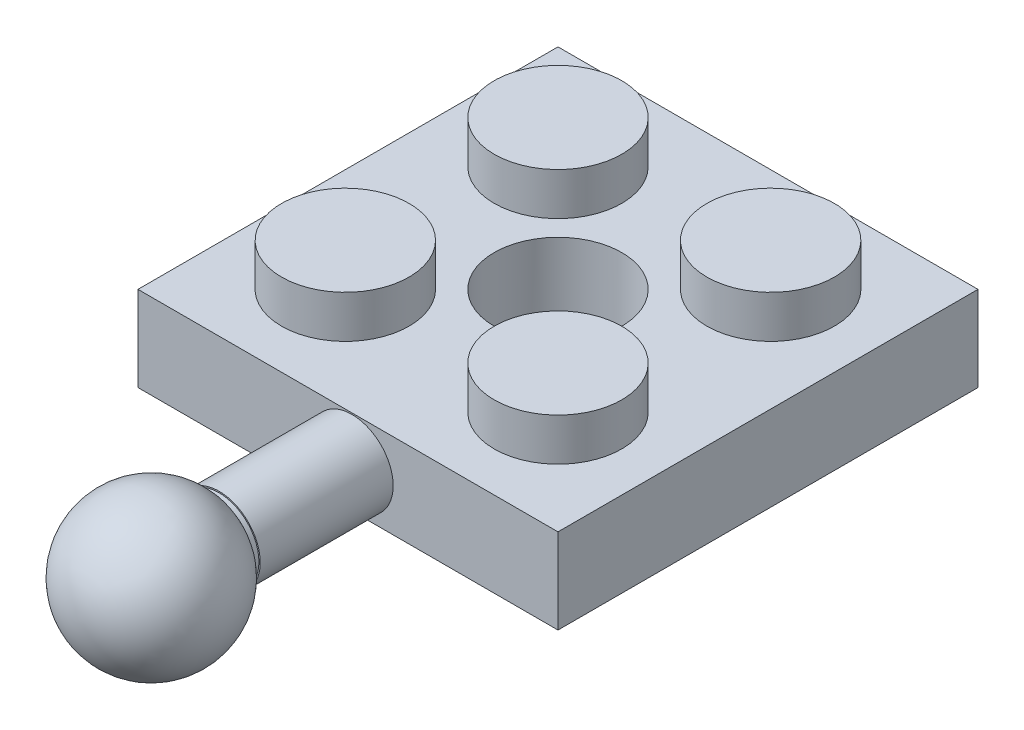
SolidWorks part; units mm, degrees
material "ABS"
ref_plane "Front Plane" through (0, 0, 0) normal (0, 0, 1) x (1, 0, 0)
ref_plane "Top Plane" through (0, 0, 0) normal (0, 1, 0) x (1, 0, 0)
ref_plane "Right Plane" through (0, 0, 0) normal (1, 0, 0) x (0, 0, -1)
sketch "Sketch1" plane through (0, 0, 0) normal (0, 0, 1) x (1, 0, 0)
  line L1 (0, 0) -> (15.8, 0)
  line L2 (0, 0) -> (0, 3.2)
  line L3 (0, 3.2) -> (15.8, 3.2)
  line L4 (15.8, 0) -> (15.8, 3.2)
  line L5 (0, 0) -> (15.8, 3.2) construction
  line L6 (0, 3.2) -> (15.8, 0) construction
  point P4 (7.9, 1.6)
  dimension "D1" = 15.8
  dimension "D2" = 3.2
extrude "Boss-Extrude1" add sketch "Sketch1" against normal blind 15.8
sketch "Sketch2" plane through (0, 3.2, 0) normal (0, 1, 0) x (1, 0, 0)
  line L0 (15.8, 0) -> (0, 0) construction
  circle A0 centre (3.9, 3.9) radius 2.4
  dimension "D1" = 4.8
  dimension "D2" = 3.9
  dimension "D3" = 3.9
extrude "Boss-Extrude2" add sketch "Sketch2" along normal blind 1.6
pattern_linear "LPattern1" count 2 spacing 8 along (0, 0, -1) count 4 spacing 8 along (1, 0, 0) of "Boss-Extrude2"
shell "Shell1" thickness 1.2
sketch "Sketch4" plane through (0, 2, 0) normal (0, -1, 0) x (1, 0, 0)
  line L0 (0, -15.8) -> (0, 0) construction
  line L1 (0, 0) -> (15.8, 0) construction
  circle A0 centre (7.9, -7.9) radius 3.25
  circle A1 centre (7.9, -7.9) radius 2.4
  dimension "D1" = 4.8
  dimension "D2" = 6.5
  dimension "D3" = 7.9
  dimension "D4" = 7.9
extrude "Boss-Extrude3" add sketch "Sketch4" along normal offset from surface (1.8 mm away) 0.2 up to face at (7.9, 0, -7.9)
sketch "Sketch6" plane through (0, 2, 0) normal (0, -1, 0) x (1, 0, 0)
  circle A0 centre (7.9, -7.9) radius 2.4 construction
  circle A1 centre (7.9, -7.9) radius 2.4
extrude "Cut-Extrude1" cut sketch "Sketch6" against normal through all
sketch "Sketch11" plane through (0, 0, 0) normal (0, 0, 1) x (1, 0, 0)
  line L0 (0, 3.2) -> (0, 0) construction
  line L1 (15.8, 3.2) -> (0, 3.2) construction
  circle A0 centre (8.05, 1.6) radius 1.55
  dimension "D1" = 3.1
  dimension "D3" = 1.6
  dimension "D2" = 8.05
extrude "Boss-Extrude5" add sketch "Sketch11" along normal blind 5
ref_plane "Plane3" through (0, 0, 7.55) normal (0, 0, 1) x (1, 0, 0)
sketch "Sketch12" plane through (0, 0, 7.55) normal (0, 0, 1) x (1, 0, 0)
  line L0 (8.05, 3.15) -> (8.05, 0.05) construction
  line L1 (8.05, 4.4) -> (8.05, -1.2)
  arc A0 (8.05, 4.4) -> (8.05, -1.2) centre (8.05, 1.6) ccw
  circle A2 centre (8.05, 1.6) radius 1.55
  arc A3 (8.05, 3.15) -> (8.05, 0.05) centre (8.05, 1.6) ccw construction
  dimension "D2" = 5.6
  dimension "D1" = 0
revolve "Revolve1" add sketch "Sketch12" angle 360 about L0
sketch "Sketch14" plane through (0, 0, 5) normal (0, 0, 1) x (1, 0, 0)
  circle A0 centre (8.05, 1.6) radius 1.5
  circle A1 centre (8.05, 1.6) radius 1.55
  circle A2 centre (8.05, 1.6) radius 1.55 construction
  dimension "D2" = 3
  dimension "D1" = 0
extrude "Boss-Extrude7" add sketch "Sketch14" along normal up to next
